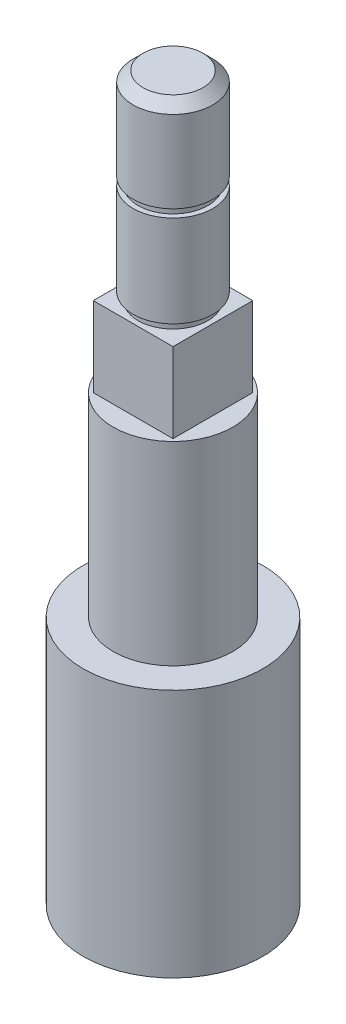
SolidWorks part; units mm, degrees
material "1060 合金"
ref_plane "前视基准面" through (0, 0, 0) normal (0, 0, 1) x (1, 0, 0)
ref_plane "上视基准面" through (0, 0, 0) normal (0, 1, 0) x (1, 0, 0)
ref_plane "右视基准面" through (0, 0, 0) normal (1, 0, 0) x (0, 0, -1)
sketch "草图1" plane through (0, 0, 0) normal (0, 1, 0) x (1, 0, 0)
  circle A0 centre (0, 0) radius 9
  dimension "D2" = 18
extrude "凸台-拉伸1" add sketch "草图1" along normal blind 25
sketch "草图2" plane through (0, 0, 0) normal (0, -1, 0) x (1, 0, 0)
  circle A0 centre (0, 0) radius 4
  dimension "D1" = 8
extrude "切除-拉伸1" cut sketch "草图2" against normal blind 20
sketch "草图6" plane through (0, 25, 0) normal (0, 1, 0) x (1, 0, 0)
  circle A0 centre (0, 0) radius 6
  dimension "D1" = 12
extrude "凸台-拉伸4" add sketch "草图6" along normal blind 19.5
sketch "草图3" plane through (0, 44.5, 0) normal (0, 1, 0) x (1, 0, 0)
  line L1 (-4, 4) -> (4, 4)
  line L2 (-4, 4) -> (-4, -4)
  line L3 (-4, -4) -> (4, -4)
  line L4 (4, 4) -> (4, -4)
  point P4 (4, 0)
  point P6 (0, 4)
  dimension "D1" = 8
extrude "凸台-拉伸2" add sketch "草图3" along normal blind 8
sketch "草图4" plane through (0, 52.5, 0) normal (0, 1, 0) x (1, 0, 0)
  circle A0 centre (0, 0) radius 4
  dimension "D1" = 8
extrude "凸台-拉伸3" add sketch "草图4" along normal blind 20
sketch "草图5" plane through (0, 0, 0) normal (1, 0, 0) x (0, 0, -1)
  circle A0 centre (0, 10) radius 1.5
  dimension "D1" = 3
  dimension "D2" = 10
extrude "切除-拉伸2" cut sketch "草图5" against normal through all
chamfer "倒角1" distance 1 angle 45 1 edges at (0, 72.5, 4)
sketch "草图7" plane through (0, 0, 0) normal (1, 0, 0) x (0, 0, -1)
  line L0 (4, 52.5) -> (4, 71.5) construction
  line L1 (4, 63.3) -> (3.5, 63.3)
  line L2 (4, 63.3) -> (4, 62.5)
  line L3 (4, 62.5) -> (3.5, 62.5)
  line L4 (3.5, 63.3) -> (3.5, 62.5)
  line L5 (3, 72.5) -> (-3, 72.5) construction
  line L6 (0, 72.5) -> (0, 49.0329) construction
  line L8 (4, 52.5) -> (3.5, 52.5)
  line L9 (4, 52.5) -> (4, 53.3)
  line L10 (4, 53.3) -> (3.5, 53.3)
  line L11 (3.5, 52.5) -> (3.5, 53.3)
  point P16 (3.75, 53.3)
  dimension "D2" = 10
  dimension "D3" = 0.5
  dimension "D4" = 0.8
revolve "切除-旋转1" cut sketch "草图7" angle 360 about L6
